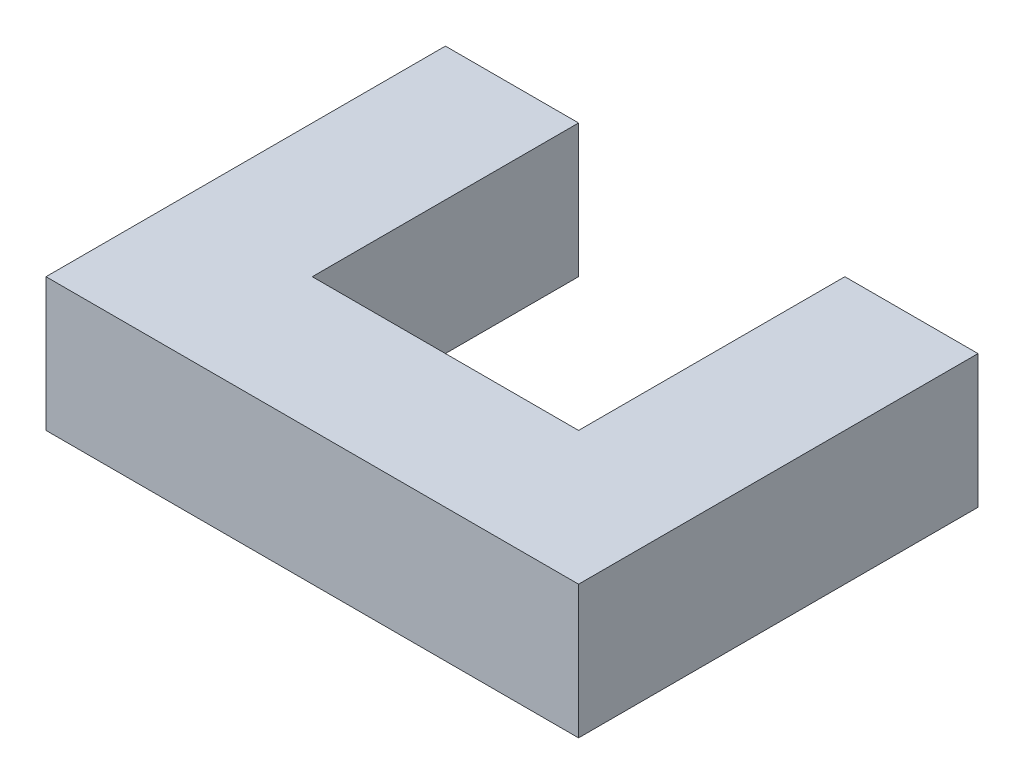
SolidWorks part; units mm, degrees
ref_plane "Front Plane" through (0, 0, 0) normal (0, 0, 1) x (1, 0, 0)
ref_plane "Top Plane" through (0, 0, 0) normal (0, 1, 0) x (1, 0, 0)
ref_plane "Right Plane" through (0, 0, 0) normal (1, 0, 0) x (0, 0, -1)
sketch "Sketch1" plane through (0, 0, 0) normal (0, 1, 0) x (1, 0, 0)
  line L0 (0, 0) -> (-40, 0)
  line L1 (-40, 0) -> (-40, 30)
  line L2 (-40, 30) -> (-30, 30)
  line L3 (-30, 30) -> (-30, 10)
  line L4 (-30, 10) -> (-10, 10)
  line L5 (-10, 10) -> (-10, 30)
  line L6 (-10, 30) -> (0, 30)
  line L7 (0, 30) -> (0, 0)
  dimension "D1" = 10
  dimension "D2" = 10
  dimension "D3" = 40
  dimension "D4" = 30
extrude "Boss-Extrude1" add sketch "Sketch1" along normal blind 10
